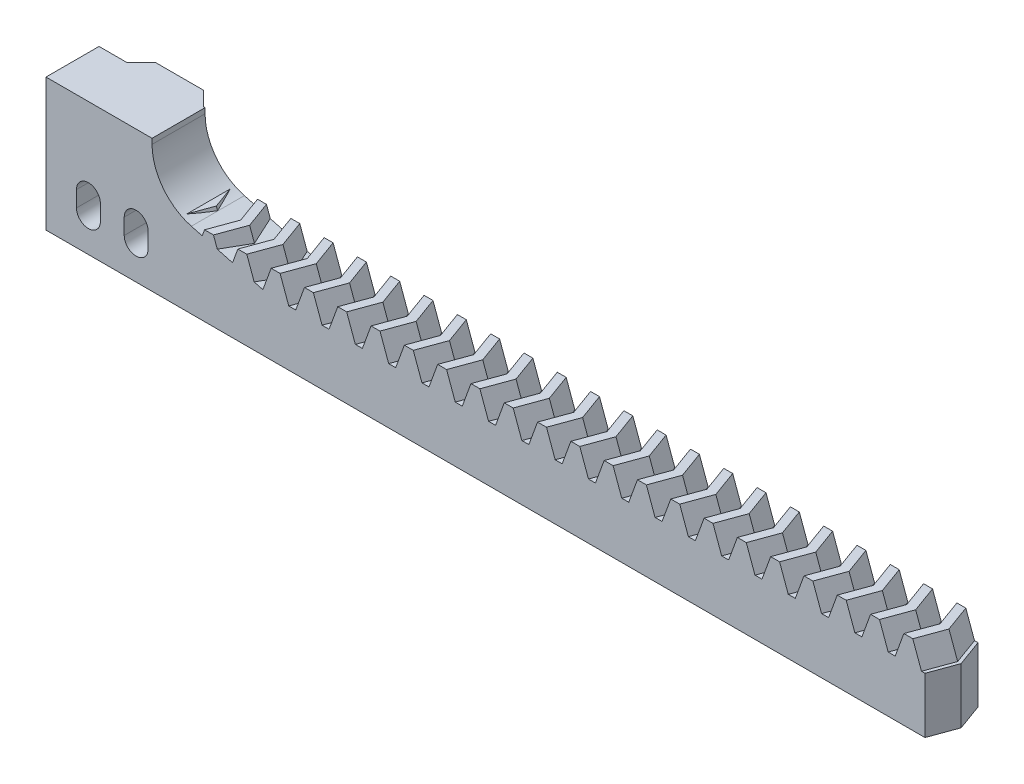
SolidWorks part; units mm, degrees
material "3D printed plastic"
ref_plane "Front Plane" through (0, 0, 0) normal (0, 0, 1) x (1, 0, 0)
ref_plane "Top Plane" through (0, 0, 0) normal (0, 1, 0) x (1, 0, 0)
ref_plane "Right Plane" through (0, 0, 0) normal (1, 0, 0) x (0, 0, -1)
sketch "Sketch1" plane through (0, 0, 0) normal (0, 0, 1) x (1, 0, 0)
  line L21 (-3.14, -10.5) -> (3.14, -10.5)
  line L22 (3.14, -10.5) -> (3.14, 0)
  line L23 (3.14, 0) -> (2.4799, 0)
  line L24 (2.4799, 0) -> (0.8421, 4.5)
  line L25 (0.8421, 4.5) -> (-0.8421, 4.5)
  line L26 (-0.8421, 4.5) -> (-2.4799, 0)
  line L27 (-2.4799, 0) -> (-3.14, 0)
  line L28 (-3.14, 0) -> (-3.14, -10.5)
  line L29 (0, -10.5) -> (0, 4.5) construction
  line L30 (-2.4799, 0) -> (2.4799, 0) construction
  line L31 (-1.57, 2.5) -> (-3.14, 2.5) construction
  line L32 (-1.57, 2.5) -> (0, 2.5) construction
  line L33 (0, 2.5) -> (1.57, 2.5) construction
  line L34 (1.57, 2.5) -> (3.14, 2.5) construction
  line L35 (3.14, 2.5) -> (3.14, 0) construction
  line L36 (-3.14, 2.5) -> (-3.14, 0) construction
  line L37 (-3.14, 0) -> (-3.126, -0.0106) construction
  dimension "D7" = 20
  dimension "D8" = 4.5
  dimension "D9" = 6.28
  dimension "D10" = 2
  dimension "D11" = 10.5
sketch "Sketch2" plane through (0, 0, 0) normal (0, 1, 0) x (1, 0, 0)
  line L0 (0, 0) -> (-1.8199, 5)
  line L1 (-2.4799, 0) -> (2.4799, 0) construction
  dimension "D1" = 70
  dimension "D2" = 5
sweep "Sweep1" add profiles "Sketch1" path "Sketch2"
mirror "Mirror2" about plane through (0, 0, 0) normal (0, 0, 1) of "Sweep1"
pattern_linear "LPattern2" count 24 spacing 6.28 along (1, 0, 0) of "Mirror2", "Sweep1"
sketch "Sketch3" plane through (0, 0, 5) normal (0, 0, 1) x (1, 0, 0)
  line L0 (0, 13.5) -> (0, 14.5)
  line L1 (0, -10.5) -> (-20, -10.5)
  line L3 (0, -10.5) -> (0, 0) construction
  line L4 (21.7457, 0) -> (21.7457, -10.5)
  line L5 (0, 14.5) -> (-20, 14.5)
  line L6 (-20, 14.5) -> (-20, -10.5)
  line L7 (-4.9599, -10.5) -> (145.7601, -10.5) construction
  line L8 (21.7457, -10.5) -> (0, -10.5)
  line L10 (19.5001, 0) -> (21.3199, 0) construction
  line L11 (7.4118, 3.8407) -> (21.7457, 0)
  arc A0 (0, 13.5) -> (7.4118, 3.8407) centre (10, 13.5) ccw
  dimension "D3" = 13.5
  dimension "D4" = 10
  dimension "D1" = 20
  dimension "D2" = 25
  dimension "D5" = 105
extrude "Boss-Extrude1" add sketch "Sketch3" against normal up to surface (10 mm away)
sketch "Sketch4" plane through (0, 14.5, 0) normal (0, 1, 0) x (1, 0, 0)
  line L0 (-14.7, 5) -> (-12, 7.7)
  line L1 (-20, 5) -> (0, 5) construction
  line L2 (-12, 7.7) -> (-3, 7.7)
  line L3 (-3, 7.7) -> (-0.3, 5)
  line L4 (-0.3, 5) -> (-14.7, 5)
  line L5 (-20, 5) -> (-20, -5) construction
  dimension "D1" = 5.3
  dimension "D2" = 45
  dimension "D3" = 2.7
  dimension "D4" = 14.4
extrude "Boss-Extrude2" add sketch "Sketch4" against normal up to surface (25 mm away)
sketch "Sketch5" plane through (0, 0, 5) normal (0, 0, 1) x (1, 0, 0)
  line L0 (-20, 14.5) -> (-20, -10.5) construction
  line L1 (-12, -10.5) -> (-14.7, -10.5) construction
  line L3 (-12, -2.5) -> (-3, -2.5) construction
  line L4 (-12, -4) -> (-12, -1) construction
  line L5 (-14.25, -4) -> (-14.25, -1)
  line L6 (-9.75, -4) -> (-9.75, -1)
  line L7 (-3, -4) -> (-3, -1) construction
  line L8 (-5.25, -4) -> (-5.25, -1)
  line L9 (-0.75, -4) -> (-0.75, -1)
  circle A0 centre (-12, -2.5) radius 2.25 construction
  circle A1 centre (-3, -2.5) radius 2.25 construction
  arc A2 (-14.25, -4) -> (-9.75, -4) centre (-12, -4) ccw
  arc A3 (-9.75, -1) -> (-14.25, -1) centre (-12, -1) ccw
  arc A4 (-5.25, -4) -> (-0.75, -4) centre (-3, -4) ccw
  arc A5 (-0.75, -1) -> (-5.25, -1) centre (-3, -1) ccw
  point P4 (-13.35, -10.5)
  point P11 (-12, -2.5)
  point P17 (-3, -2.5)
  dimension "D2" = 8
  dimension "D3" = 4.5
  dimension "D1" = 8
  dimension "D4" = 9
  dimension "D5" = 3
extrude "Cut-Extrude1" cut sketch "Sketch5" against normal through all
